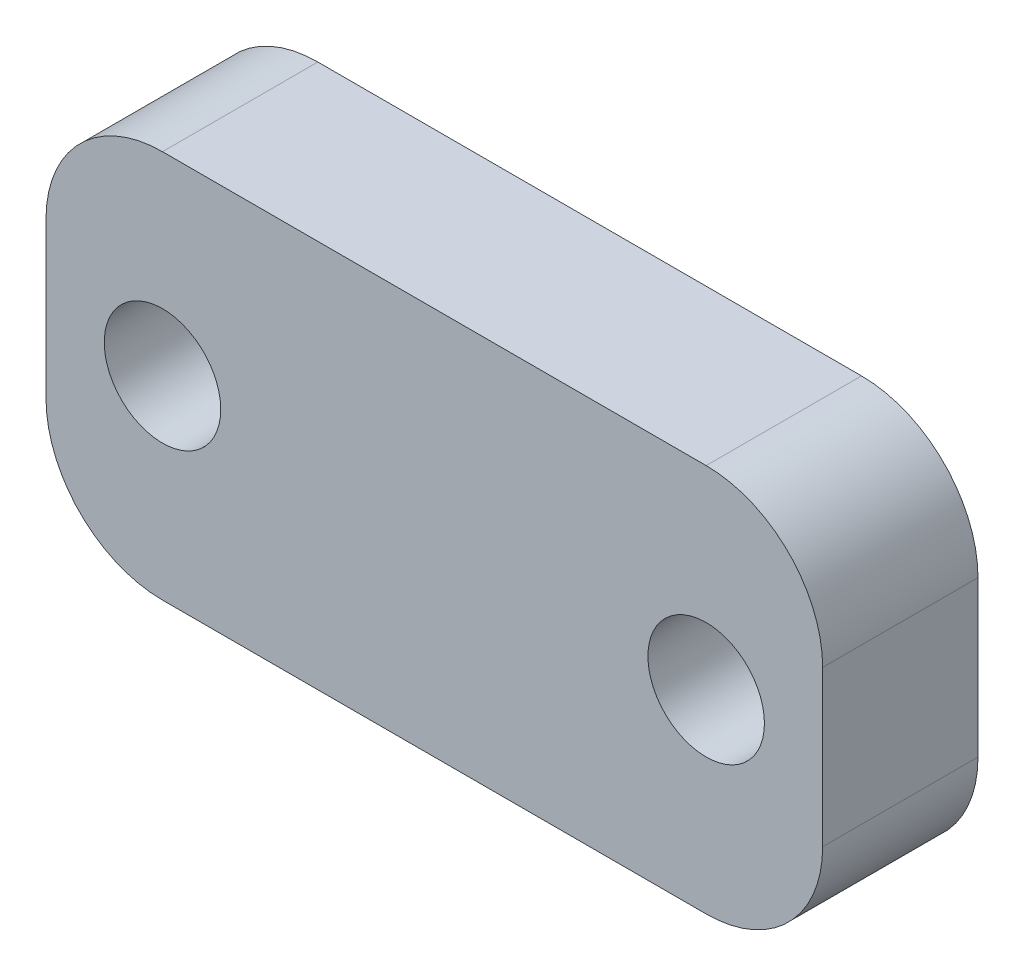
SolidWorks part; units mm, degrees
ref_plane "前视基准面" through (0, 0, 0) normal (0, 0, 1) x (1, 0, 0)
ref_plane "上视基准面" through (0, 0, 0) normal (0, 1, 0) x (1, 0, 0)
ref_plane "右视基准面" through (0, 0, 0) normal (1, 0, 0) x (0, 0, -1)
sketch "草图1" plane through (0, 0, 0) normal (0, 0, 1) x (1, 0, 0)
  line L1 (-7, 5) -> (7, 5)
  line L2 (-10, 2) -> (-10, -2)
  line L3 (-7, -5) -> (7, -5)
  line L4 (10, 2) -> (10, -2)
  line L5 (-10, 5) -> (10, -5) construction
  line L6 (-10, -5) -> (10, 5) construction
  circle A0 centre (-7, 0) radius 1.5
  circle A1 centre (7, 0) radius 1.5
  arc A2 (-10, -2) -> (-7, -5) centre (-7, -2) ccw
  arc A3 (7, -5) -> (10, -2) centre (7, -2) ccw
  arc A4 (7, 5) -> (10, 2) centre (7, 2) cw
  arc A5 (-7, 5) -> (-10, 2) centre (-7, 2) ccw
  point P0 (0, 0)
  dimension "D3" = 3
  dimension "D5" = 3
  dimension "D1" = 20
  dimension "D2" = 10
  dimension "D4" = 3
extrude "凸台-拉伸1" add sketch "草图1" along normal blind 4
